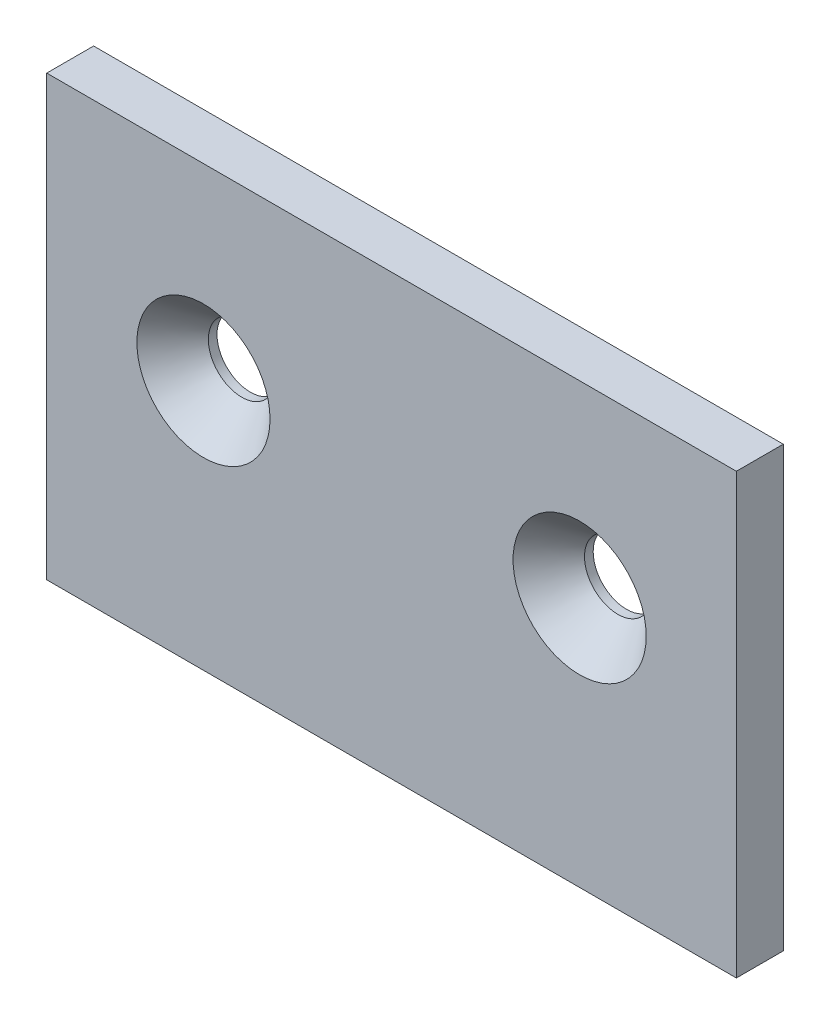
SolidWorks part; units mm, degrees
ref_plane "Front" through (0, 0, 0) normal (0, 0, 1) x (1, 0, 0)
ref_plane "Top" through (0, 0, 0) normal (0, 1, 0) x (1, 0, 0)
ref_plane "Right" through (0, 0, 0) normal (1, 0, 0) x (0, 0, -1)
sketch "Sketch1" plane through (0, 0, 0) normal (0, 0, 1) x (1, 0, 0)
  line L1 (34.925, 22.225) -> (-34.925, 22.225)
  line L2 (34.925, 22.225) -> (34.925, -22.225)
  line L3 (34.925, -22.225) -> (-34.925, -22.225)
  line L4 (-34.925, 22.225) -> (-34.925, -22.225)
  line L5 (34.925, 22.225) -> (-34.925, -22.225) construction
  line L6 (34.925, -22.225) -> (-34.925, 22.225) construction
  point P0 (0, 0)
  dimension "D1" = 44.45
  dimension "D2" = 69.85
extrude "Boss-Extrude1" add sketch "Sketch1" along normal blind 4.7498
hole_wizard "CSK for 1/4 Flat Head Socket Cap Screw1" positions "Sketch2" profile "Sketch3" countersink size "1/4" standard "ANSI Inch" end condition up to next
sketch "Sketch2" plane through (0, 0, 4.7498) normal (0, 0, 1) x (1, 0, 0)
  line L0 (-34.925, -22.225) -> (34.925, -22.225) construction
  line L1 (-34.925, 22.225) -> (-34.925, -22.225) construction
  point P0 (-19.05, 3.175)
  point P2 (19.05, 3.175)
  point P9 (0, 0)
  dimension "D1" = 25.4
  dimension "D2" = 38.1
  dimension "D3" = 15.875
sketch "Sketch3" plane through (-19.05, 3.175, 4.7498) normal (1, 0, 0) x (0, -1, 0)
  line L0 (0, 0) -> (0, 4.7498)
  line L1 (0, 4.7498) -> (3.3782, 4.7498)
  line L2 (3.3782, 4.7498) -> (3.3782, 3.8716)
  line L3 (3.3782, 3.8716) -> (6.7437, 0)
  line L5 (6.7437, 0) -> (0, 0)
  line L6 (-3.3782, 3.8716) -> (-6.7437, 0) construction
  line L11 (0, -6.35) -> (0, 107.95) construction
  dimension "Thru Hole Dia." = 6.7564
  dimension "Thru Hole Depth" = 4.7498
  dimension "Near C'Sink Dia." = 13.4874
  dimension "Near C'Sink Angle" = 82
